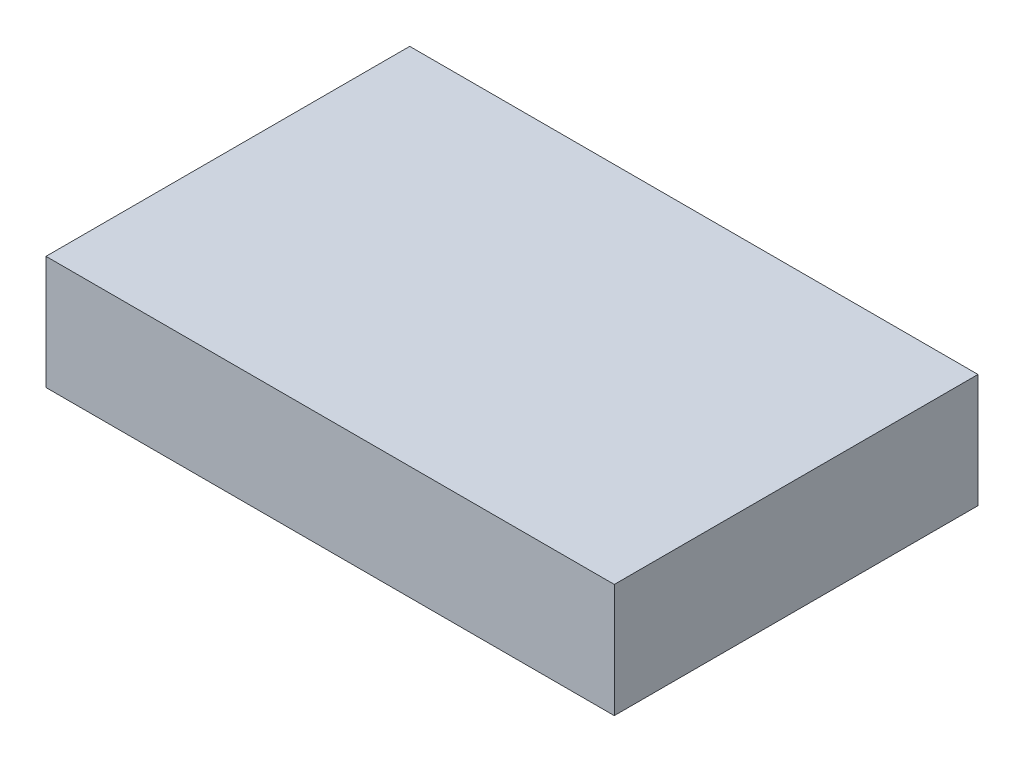
SolidWorks part; units mm, degrees
ref_plane "Front Plane" through (0, 0, 0) normal (0, 0, 1) x (1, 0, 0)
ref_plane "Top Plane" through (0, 0, 0) normal (0, 1, 0) x (1, 0, 0)
ref_plane "Right Plane" through (0, 0, 0) normal (1, 0, 0) x (0, 0, -1)
sketch "Sketch1" plane through (0, 0, 0) normal (0, 1, 0) x (1, 0, 0)
  line L1 (0, 0) -> (5, 0)
  line L2 (0, 0) -> (0, 3.2)
  line L3 (0, 3.2) -> (5, 3.2)
  line L4 (5, 0) -> (5, 3.2)
  dimension "D1" = 5
  dimension "D2" = 3.2
extrude "Boss-Extrude1" add sketch "Sketch1" along normal blind 0.8
sketch "Sketch2" plane through (0, 0.8, 0) normal (0, 1, 0) x (1, 0, 0)
  line L1 (0, 3.2) -> (5, 3.2)
  line L2 (0, 3.2) -> (0, 0)
  line L3 (0, 0) -> (5, 0)
  line L4 (5, 3.2) -> (5, 0)
extrude "Boss-Extrude2" add sketch "Sketch2" along normal blind 0.2
